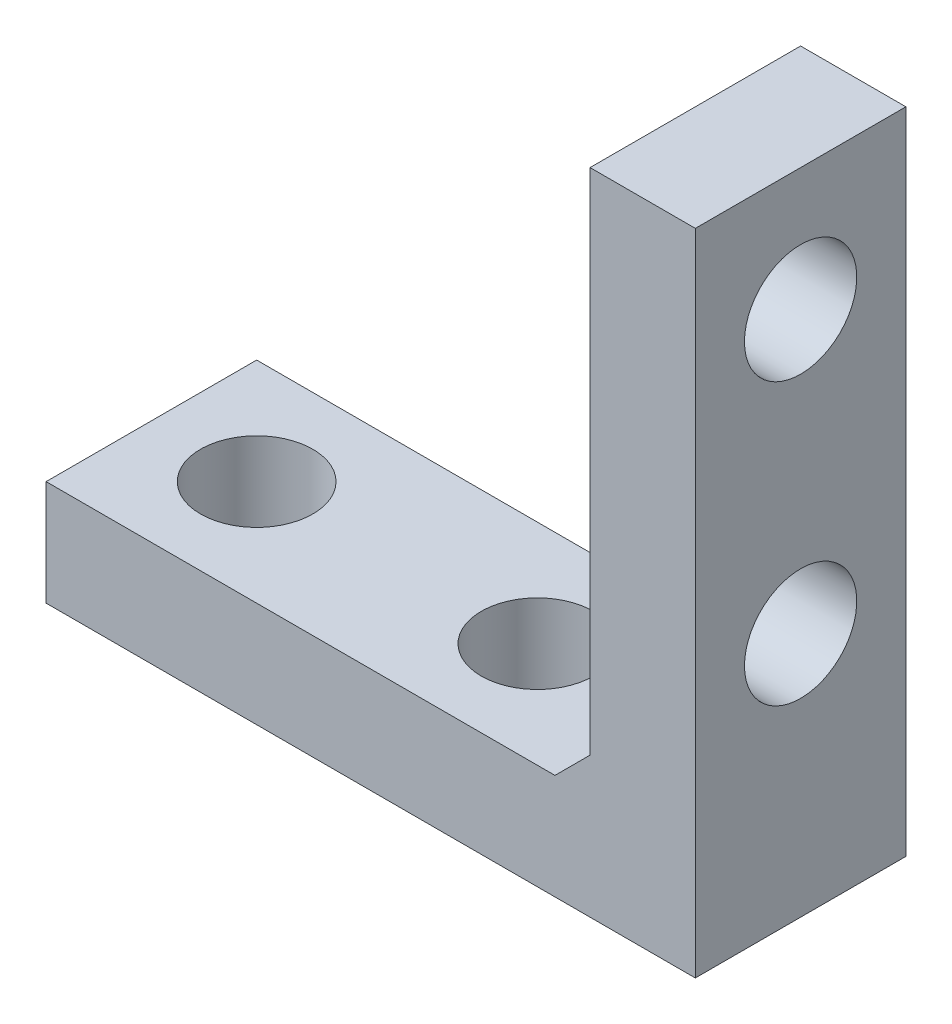
SolidWorks part; units mm, degrees
ref_plane "Front Plane" through (0, 0, 0) normal (0, 0, 1) x (1, 0, 0)
ref_plane "Top Plane" through (0, 0, 0) normal (0, 1, 0) x (1, 0, 0)
ref_plane "Right Plane" through (0, 0, 0) normal (1, 0, 0) x (0, 0, -1)
sketch "Sketch1" plane through (0, 0, 0) normal (0, 1, 0) x (1, 0, 0)
  line L1 (-9.25, -3) -> (9.25, -3)
  line L2 (-9.25, -3) -> (-9.25, 3)
  line L3 (-9.25, 3) -> (9.25, 3)
  line L4 (9.25, -3) -> (9.25, 3)
  line L5 (0, 3) -> (0, -3) construction
  line L6 (-9.25, 0) -> (9.25, 0) construction
  circle A0 centre (-6.25, 0) radius 1.6
  circle A1 centre (1.75, 0) radius 1.6
  point P0 (0, 0)
  dimension "D4" = 3.2
  dimension "D5" = 3.2
  dimension "D1" = 18.5
  dimension "D2" = 6
  dimension "D3" = 3
  dimension "D6" = 8
extrude "Boss-Extrude1" add sketch "Sketch1" along normal blind 3
sketch "Sketch2" plane through (0, 3, 0) normal (0, 1, 0) x (1, 0, 0)
  line L0 (9.25, 3) -> (9.25, -3)
  line L1 (9.25, 3) -> (6.25, 3)
  line L2 (9.25, -3) -> (6.25, -3)
  line L3 (6.25, 3) -> (6.25, -3)
  dimension "D1" = 3
extrude "Boss-Extrude2" add sketch "Sketch2" along normal blind 15.5
sketch "Sketch3" plane through (6.25, 0, 0) normal (-1, 0, 0) x (0, 0, 1)
  line L0 (0, 18.5) -> (0, 3) construction
  line L1 (-3, 18.5) -> (3, 18.5) construction
  line L2 (-3, 3) -> (3, 3) construction
  circle A0 centre (0, 7) radius 1.6
  circle A1 centre (0, 15) radius 1.6
  dimension "D1" = 3.2
  dimension "D4" = 8
  dimension "D2" = 4
  dimension "D3" = 2
extrude "Cut-Extrude1" cut sketch "Sketch3" against normal through all
ref_plane "Plane1" through (6.25, 3, 3) normal (0, 0, 1) x (1, 0, 0)
sketch "Sketch5" plane through (6.25, 3, 3) normal (0, 0, 1) x (1, 0, 0)
  line L0 (-1, 0) -> (0, 1)
  line L1 (-15.5, 0) -> (0, 0) construction
  line L2 (0, 15.5) -> (0, 0) construction
  line L3 (0, 1) -> (0, 0)
  line L4 (0, 0) -> (-1, 0)
  dimension "D1" = 135
  dimension "D2" = 1
extrude "Boss-Extrude3" add sketch "Sketch5" against normal blind 6
